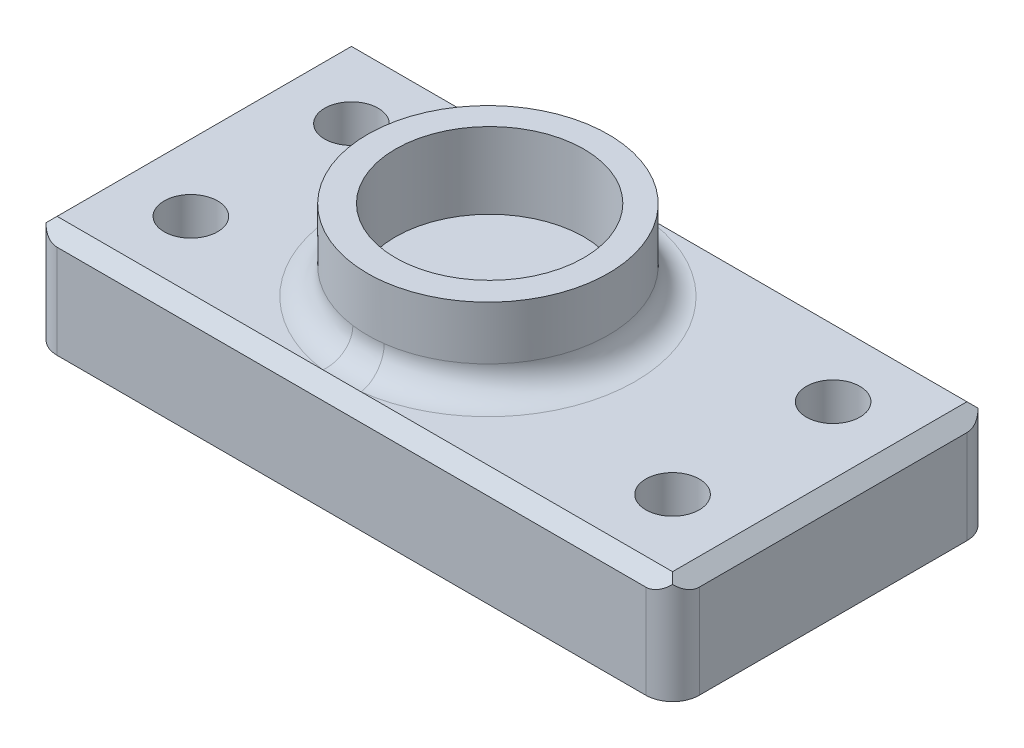
SolidWorks part; units mm, degrees
ref_plane "Front Plane" through (0, 0, 0) normal (0, 0, 1) x (1, 0, 0)
ref_plane "Top Plane" through (0, 0, 0) normal (0, 1, 0) x (1, 0, 0)
ref_plane "Right Plane" through (0, 0, 0) normal (1, 0, 0) x (0, 0, -1)
sketch "Sketch3" plane through (0, 0, 0) normal (0, 1, 0) x (1, 0, 0)
  line L1 (-69.458, 42.0897) -> (82.942, 42.0897)
  line L2 (-69.458, 42.0897) -> (-69.458, -34.1103)
  line L3 (-69.458, -34.1103) -> (82.942, -34.1103)
  line L4 (82.942, 42.0897) -> (82.942, -34.1103)
  dimension "D1" = 152.4
  dimension "D2" = 76.2
extrude "Boss-Extrude2" add sketch "Sketch3" along normal blind 25.4
sketch "Sketch4" plane through (0, 25.4, 0) normal (0, 1, 0) x (1, 0, 0)
  line L0 (-69.458, -34.1103) -> (82.942, -34.1103) construction
  line L1 (82.942, -34.1103) -> (82.942, 42.0897) construction
  line L2 (82.942, 42.0897) -> (-69.458, 42.0897) construction
  line L3 (-69.458, 42.0897) -> (-69.458, -34.1103) construction
  circle A0 centre (-50.408, 23.0397) radius 6.35
  circle A1 centre (-50.408, -15.0603) radius 6.35
  circle A2 centre (63.892, 23.0397) radius 6.35
  circle A3 centre (63.892, -15.0603) radius 6.35
  point P12 (63.892, 25.4535)
  point P15 (63.892, 23.0397)
  point P16 (-52.7425, 23.0397)
  point P19 (-50.408, -15.0603)
  dimension "D5" = 12.7
  dimension "D1" = 19.05
  dimension "D2" = 19.05
  dimension "D3" = 19.05
  dimension "D4" = 19.05
extrude "Cut-Extrude1" cut sketch "Sketch4" against normal through all
sketch "Sketch5" plane through (0, 25.4, 0) normal (0, 1, 0) x (1, 0, 0)
  circle A0 centre (1.3277, 3.6931) radius 28.575
  circle A1 centre (1.3277, 3.6931) radius 15.875
  dimension "D1" = 57.15
  dimension "D2" = 31.75
extrude "Boss-Extrude3" add sketch "Sketch5" along normal blind 19.05 contours A0
sketch "Sketch6" plane through (0, 44.45, 0) normal (0, 1, 0) x (1, 0, 0)
  circle A1 centre (1.4408, 3.9892) radius 22.3533
extrude "Cut-Extrude3" cut sketch "Sketch6" against normal blind 18.034
chamfer "Chamfer1" distance 3.175 angle 45 4 edges at (-69.458, 25.4, -3.9897) (6.742, 25.4, -42.0897) (82.942, 25.4, -3.9897) (6.742, 25.4, 34.1103)
fillet "Fillet1" radius 6.35 5 edges at (82.942, 11.1125, -42.0897) (1.3277, 25.4, 24.8819) (-69.458, 11.1125, -42.0897) (-69.458, 11.1125, 34.1103) (82.942, 11.1125, 34.1103)
